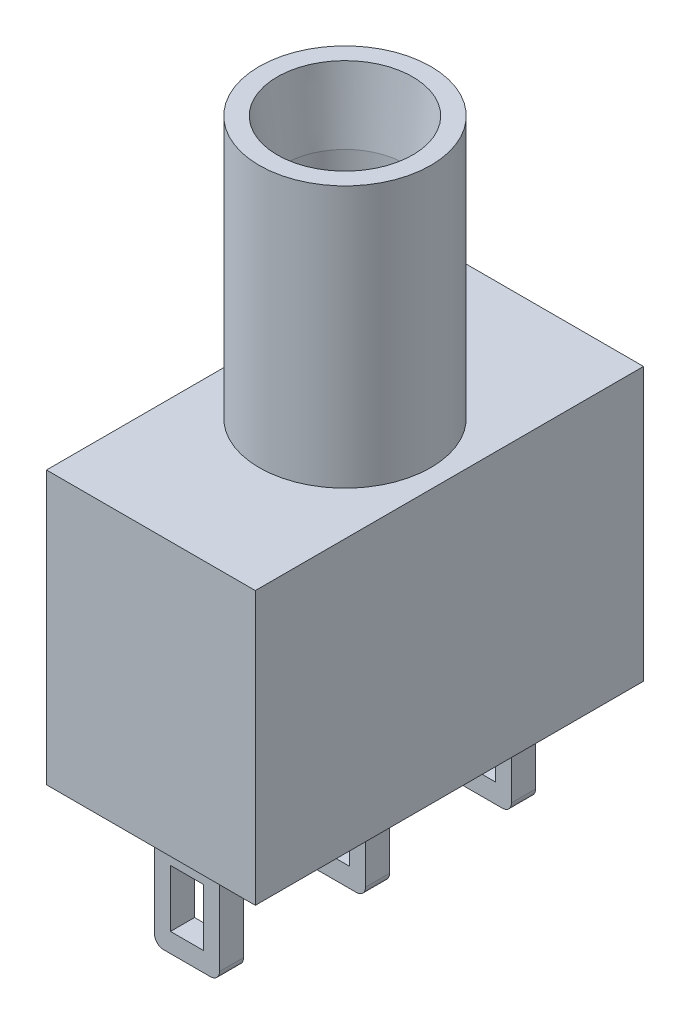
SolidWorks part; units mm, degrees
ref_plane "Plan de face" through (0, 0, 0) normal (0, 0, 1) x (1, 0, 0)
ref_plane "Plan de dessus" through (0, 0, 0) normal (0, 1, 0) x (1, 0, 0)
ref_plane "Plan de droite" through (0, 0, 0) normal (1, 0, 0) x (0, 0, -1)
sketch "Esquisse1" plane through (0, 0, 0) normal (0, 1, 0) x (1, 0, 0)
  line L1 (0, 0) -> (6.94, 0)
  line L2 (0, 0) -> (0, 12.9)
  line L3 (0, 12.9) -> (6.94, 12.9)
  line L4 (6.94, 0) -> (6.94, 12.9)
  dimension "D1" = 12.9
  dimension "D2" = 6.94
extrude "Boss.-Extru.1" add sketch "Esquisse1" along normal blind 9.06
sketch "Esquisse2" plane through (0, 9.06, 0) normal (0, 1, 0) x (1, 0, 0)
  line L0 (3.47, 12.9) -> (3.47, 0) construction
  line L1 (6.94, 12.9) -> (0, 12.9) construction
  line L2 (0, 0) -> (6.94, 0) construction
  circle A0 centre (3.47, 6.45) radius 2.85
  dimension "D1" = 5.7
extrude "Boss.-Extru.2" add sketch "Esquisse2" along normal blind 8.7
sketch "Esquisse3" plane through (0, 17.76, 0) normal (0, 1, 0) x (1, 0, 0)
  circle A0 centre (3.47, 6.45) radius 2
  dimension "D1" = 4
extrude "Enlèv. mat.-Extru.1" cut sketch "Esquisse3" against normal blind 8.7
sketch "Esquisse4" plane through (0, 0, 0) normal (-1, 0, 0) x (0, 0, 1)
  line L0 (-6.45, 0) -> (-6.45, 19.6396) construction
  line L1 (-12.9, 0) -> (0, 0) construction
  line L2 (-3.6, 17.76) -> (-9.3, 17.76) construction
  circle A0 centre (-6.4533, 14.76) radius 0.5
  dimension "D2" = 1
  dimension "D1" = 3
extrude "Enlèv. mat.-Extru.2" cut sketch "Esquisse4" against normal blind 2.5 and the other way blind 2.5 from offset 3.45 offset against normal yes
chamfer "Chanfrein1" distance 0.25 angle 84 1 edges at (3.47, 17.76, -4.45)
sketch "Esquisse5" plane through (0, 0, 0) normal (0, -1, 0) x (1, 0, 0)
  line L0 (6.94, -6.45) -> (-2.0351, -6.45) construction
  line L1 (6.94, 0) -> (6.94, -12.9) construction
  line L2 (3.47, 0) -> (3.47, -13.3292) construction
  line L3 (2.39, -1.2) -> (4.55, -1.2)
  line L4 (2.39, -1.2) -> (2.39, -2)
  line L5 (2.39, -2) -> (4.55, -2)
  line L6 (4.55, -1.2) -> (4.55, -2)
  line L7 (0, 0) -> (6.94, 0) construction
  line L8 (4.55, -11.7) -> (4.55, -10.9)
  line L9 (2.39, -10.9) -> (4.55, -10.9)
  line L10 (2.39, -11.7) -> (2.39, -10.9)
  line L11 (2.39, -11.7) -> (4.55, -11.7)
  line L13 (2.39, -6.05) -> (4.55, -6.05)
  line L14 (2.39, -6.05) -> (2.39, -6.85)
  line L15 (2.39, -6.85) -> (4.55, -6.85)
  line L16 (4.55, -6.05) -> (4.55, -6.85)
  dimension "D1" = 2.16
  dimension "D2" = 1.08
  dimension "D3" = 0.8
  dimension "D4" = 1.2
  dimension "D5" = 1.08
  dimension "D6" = 2.16
  dimension "D7" = 0.4
  dimension "D8" = 0.8
extrude "Boss.-Extru.3" add sketch "Esquisse5" along normal blind 4
fillet "Congé1" radius 0.3 6 edges at (4.55, -4, -11.3) (4.55, -4, -6.45) (4.55, -4, -1.6) (2.39, -4, -1.6) (2.39, -4, -6.45) (2.39, -4, -11.3)
sketch "Esquisse6" plane through (0, 0, -11.7) normal (0, 0, -1) x (-1, 0, 0)
  line L0 (-2.69, -4) -> (-4.25, -4) construction
  line L1 (-4.0203, -1.46) -> (-2.9203, -1.46)
  line L2 (-4.0203, -1.46) -> (-4.0203, -3.36)
  line L3 (-4.0203, -3.36) -> (-2.9203, -3.36)
  line L4 (-2.9203, -1.46) -> (-2.9203, -3.36)
  line L5 (-3.47, -4) -> (-3.47, -0.5723) construction
  dimension "D1" = 1.1
  dimension "D2" = 1.9
  dimension "D3" = 0.64
  dimension "D4" = 0.5497
extrude "Enlèv. mat.-Extru.3" cut sketch "Esquisse6" against normal through all
